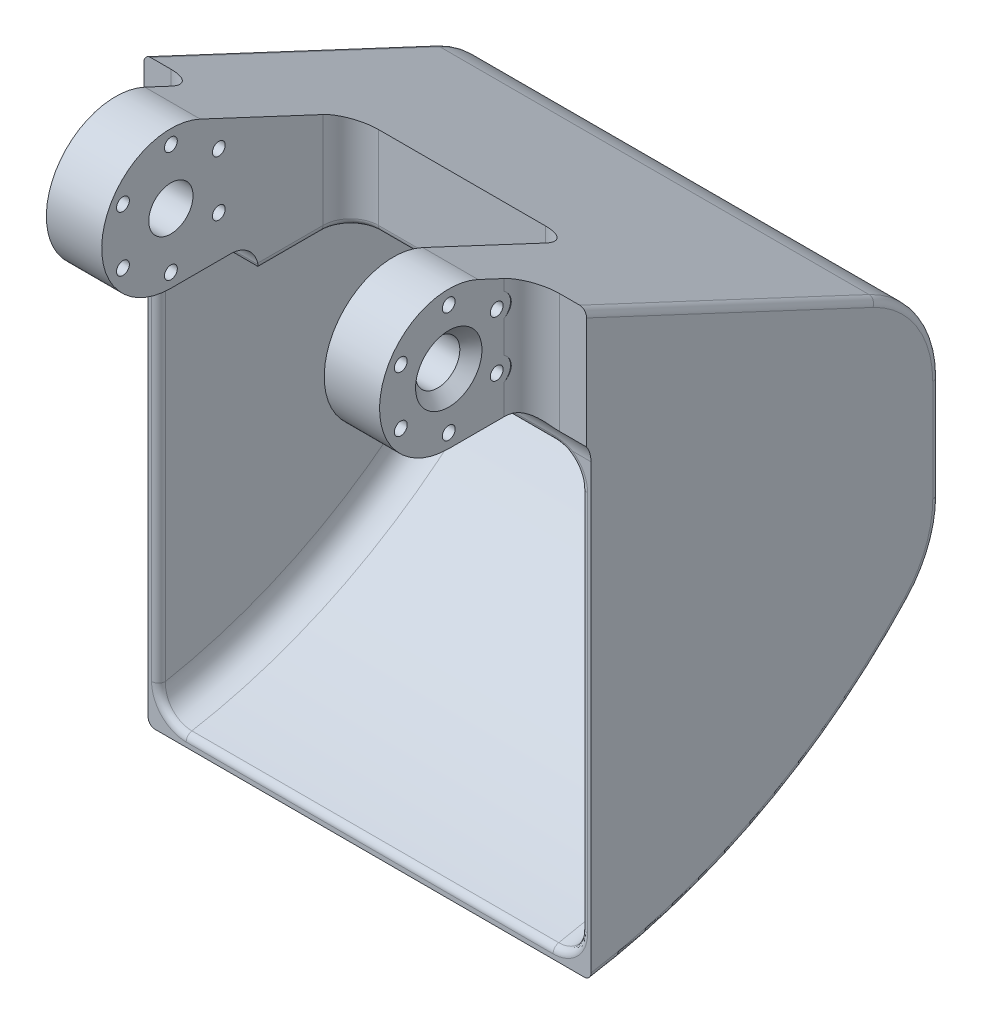
SolidWorks part; units mm, degrees
material "ABS"
ref_plane "Front Plane" through (0, 0, 0) normal (0, 0, 1) x (1, 0, 0)
ref_plane "Top Plane" through (0, 0, 0) normal (0, 1, 0) x (1, 0, 0)
ref_plane "Right Plane" through (0, 0, 0) normal (1, 0, 0) x (0, 0, -1)
sketch "Sketch1" plane through (0, 0, 0) normal (1, 0, 0) x (0, 0, -1)
  line L0 (0, 16.891) -> (16.891, 16.891) construction
  line L1 (16.891, 16.891) -> (16.891, -16.891) construction
  line L2 (16.891, -16.891) -> (0, -16.891) construction
  line L3 (20.066, 16.891) -> (20.066, -121.3752) construction
  line L4 (-105.3388, -20.066) -> (153.9666, -20.066) construction
  line L5 (100.066, -78.2036) -> (100.066, -20.066)
  line L6 (23.241, 16.891) -> (23.241, -20.066)
  line L7 (23.241, -20.066) -> (100.066, -20.066)
  line L8 (20.066, -125.4048) -> (20.066, 16.891)
  line L9 (20.066, 16.891) -> (23.241, 16.891)
  arc A0 (0, 16.891) -> (0, -16.891) centre (0, 0) ccw construction
  arc A1 (20.066, -125.4048) -> (100.066, -78.2036) centre (0, 0) ccw construction
  arc A2 (20.066, -125.4048) -> (100.066, -78.2036) centre (0, 0) ccw
  dimension "D1" = 33.782
  dimension "D4" = 127
  dimension "D2" = 3.175
  dimension "D3" = 3.175
  dimension "D5" = 3.175
  dimension "D6" = 80
extrude "Boss-Extrude1" add sketch "Sketch1" along normal blind 101.6
fillet "Fillet1" radius 25.4 2 edges at (50.8, -78.2036, -100.066) (50.8, -20.066, -100.066)
sketch "Sketch2" plane through (0, 0, -23.241) normal (0, 0, -1) x (-1, 0, 0)
  line L0 (-101.6, -20.066) -> (0, -20.066) construction
  line L1 (-101.6, 16.891) -> (0, 16.891)
  line L2 (-101.6, 16.891) -> (-101.6, -20.066)
  line L3 (-101.6, -20.066) -> (0, -20.066)
  line L4 (0, 16.891) -> (0, -20.066)
  line L5 (0, 16.891) -> (0, -125.4048) construction
extrude "Cut-Extrude1" cut sketch "Sketch2" against normal through all
shell "Shell1" thickness 2.3622
fillet "Fillet2" radius 6.35 10 edges at (99.2378, -22.4282, -47.366) (99.2378, -29.1758, -90.9562) (99.2378, -57.1842, -97.7038) (99.2378, -77.2899, -96.1227) (2.3622, -22.4282, -47.366) (2.3622, -109.7596, -59.0544) (2.3622, -77.2899, -96.1227) (2.3622, -57.1842, -97.7038) (99.2378, -109.7596, -59.0544) (2.3622, -29.1758, -90.9562)
sketch "Sketch4" plane through (101.6, 0, 0) normal (1, 0, 0) x (0, 0, -1)
  line L0 (0, -15.875) -> (20.066, -15.875)
  line L1 (20.066, -15.875) -> (20.066, -20.066)
  line L2 (20.066, -20.066) -> (20.066, -125.4048) construction
  line L3 (74.666, -20.066) -> (20.066, -20.066) construction
  line L4 (6.7299, 14.3779) -> (85.4339, -22.4614)
  line L5 (74.666, -20.066) -> (20.066, -20.066)
  arc A0 (6.7299, 14.3779) -> (0, -15.875) centre (0, 0) ccw
  arc A1 (100.066, -45.466) -> (74.666, -20.066) centre (74.666, -45.466) ccw construction
  arc A2 (85.4339, -22.4614) -> (74.666, -20.066) centre (74.666, -45.466) ccw
  dimension "D1" = 31.75
extrude "Boss-Extrude2" add sketch "Sketch4" against normal up to surface (101.6 mm away) up to face at (0, -61.262, -69.7419)
fillet "Fillet3" radius 6.35 1 edges at (50.8, -15.875, -20.066)
ref_plane "Plane1" through (0, 15.875, 0) normal (0, 1, 0) x (-1, 0, 0)
sketch "Sketch6" plane through (0, 15.875, 0) normal (0, 1, 0) x (-1, 0, 0)
  line L0 (0, 15.875) -> (-101.6, 15.875) construction
  line L1 (-76.327, -41.275) -> (-25.273, -41.275)
  line L2 (-76.327, -41.275) -> (-76.327, 15.875)
  line L3 (-76.327, 15.875) -> (-25.273, 15.875)
  line L4 (-25.273, -41.275) -> (-25.273, 15.875)
  line L5 (-76.327, -41.275) -> (-25.273, 15.875) construction
  line L6 (-76.327, 15.875) -> (-25.273, -41.275) construction
  line L8 (-50.8, -100.066) -> (-50.8, 15.875) construction
  line L9 (0, -100.066) -> (-101.6, -100.066) construction
  line L11 (-101.6, 15.875) -> (-89.027, 15.875)
  line L12 (-101.6, 15.875) -> (-101.6, -19.05)
  line L13 (-101.6, -19.05) -> (-89.027, -19.05)
  line L14 (-89.027, 15.875) -> (-89.027, -19.05)
  line L15 (0, 15.875) -> (-12.573, 15.875)
  line L16 (0, 15.875) -> (0, -19.05)
  line L17 (0, -19.05) -> (-12.573, -19.05)
  line L18 (-12.573, 15.875) -> (-12.573, -19.05)
  point P0 (-50.8, -12.7)
  dimension "D1" = 57.15
  dimension "D2" = 51.054
  dimension "D3" = 12.7
  dimension "D4" = 12.7
  dimension "D5" = 34.925
extrude "Cut-Extrude2" cut sketch "Sketch6" against normal up to next
sketch "Sketch7" plane through (89.027, 0, 0) normal (1, 0, 0) x (0, 0, -1)
  circle A0 centre (0, 0) radius 5.08
  dimension "D1" = 10.16
extrude "Cut-Extrude3" cut sketch "Sketch7" against normal through all
fillet "Fillet4" radius 6.35 4 edges at (12.573, -5.0842, -19.05) (25.273, -12.11, -41.275) (76.327, -12.11, -41.275) (89.027, -5.0842, -19.05)
fillet "Fillet5" radius 1.5875 10 edges at (0, -111.9309, -60.0039) (0, -78.1499, -98.3228) (0, -57.1842, -100.066) (0, -31.8341, -96.098) (101.6, -111.9309, -60.0039) (101.6, -78.1499, -98.3228) (101.6, -57.1842, -100.066) (101.6, -31.8341, -96.098) (0, -6.9251, -52.2419) (101.6, -6.9251, -52.2419)
fillet "Fillet6" radius 1.5875 14 edges at (76.327, -22.4282, -27.4955) (74.4671, -22.4282, -39.4151) (50.8, -22.4282, -41.275) (25.273, -22.4282, -27.4955) (84.6074, -22.4282, -20.066) (97.3779, -24.2881, -20.066) (99.2378, -72.6758, -20.066) (97.8121, -120.6396, -20.066) (16.9926, -22.4282, -20.066) (4.2221, -24.2881, -20.066) (2.3622, -72.6758, -20.066) (4.7848, -121.6336, -20.066) (27.1329, -22.4282, -39.4151) (50.8, -123.0119, -20.066)
hole_wizard "#4 Clearance Hole1" positions "Sketch9" profile "Sketch12" hole size "#4" standard "Ansi Inch"
sketch "Sketch9" plane through (89.027, 0, 0) normal (1, 0, 0) x (0, 0, -1)
  line L0 (0, 0) -> (0, 12.7) construction
  line L1 (0, 0) -> (0, 0.4466) construction
  line L3 (0, 0) -> (0, 9.3368) construction
  point P0 (0, 12.7)
  dimension "D1" = 0
  dimension "D2" = 12.7
sketch "Sketch12" plane through (89.027, 12.7, 0) normal (0, 1, 0) x (0, 0, -1)
  line L0 (0, 0) -> (0, 12.701)
  line L1 (0, 12.701) -> (1.4732, 12.701)
  line L2 (1.4732, 12.701) -> (1.4732, 0)
  line L5 (1.4732, 0) -> (0, 0)
  line L11 (0, -6.35) -> (0, 107.95) construction
  dimension "Thru Hole Dia." = 2.9464
  dimension "Thru Hole Depth" = 12.701
pattern_circular "CirPattern1" count 6 over 360 about axis through (0, 0, 0) along (1, 0, 0) of "#4 Clearance Hole1"
sketch "Sketch13" plane through (89.027, 0, 0) normal (1, 0, 0) x (0, 0, -1)
  circle A0 centre (10.9985, 6.35) radius 3.175
  circle A1 centre (10.9985, -6.35) radius 3.175
  dimension "D1" = 6.35
extrude "Cut-Extrude4" cut sketch "Sketch13" along normal up to next
ref_plane "Plane2" through (50.8, 0, 0) normal (-1, 0, 0) x (0, 0, 1)
mirror "Mirror1" about plane through (50.8, 0, 0) normal (-1, 0, 0) of "Cut-Extrude4", "CirPattern1", "#4 Clearance Hole1"
chamfer "Chamfer1" distance 2.54 angle 45 1 edges at (89.027, 0, -5.08)
chamfer "Chamfer2" distance 2.54 angle 45 1 edges at (12.573, 0, -5.08)
